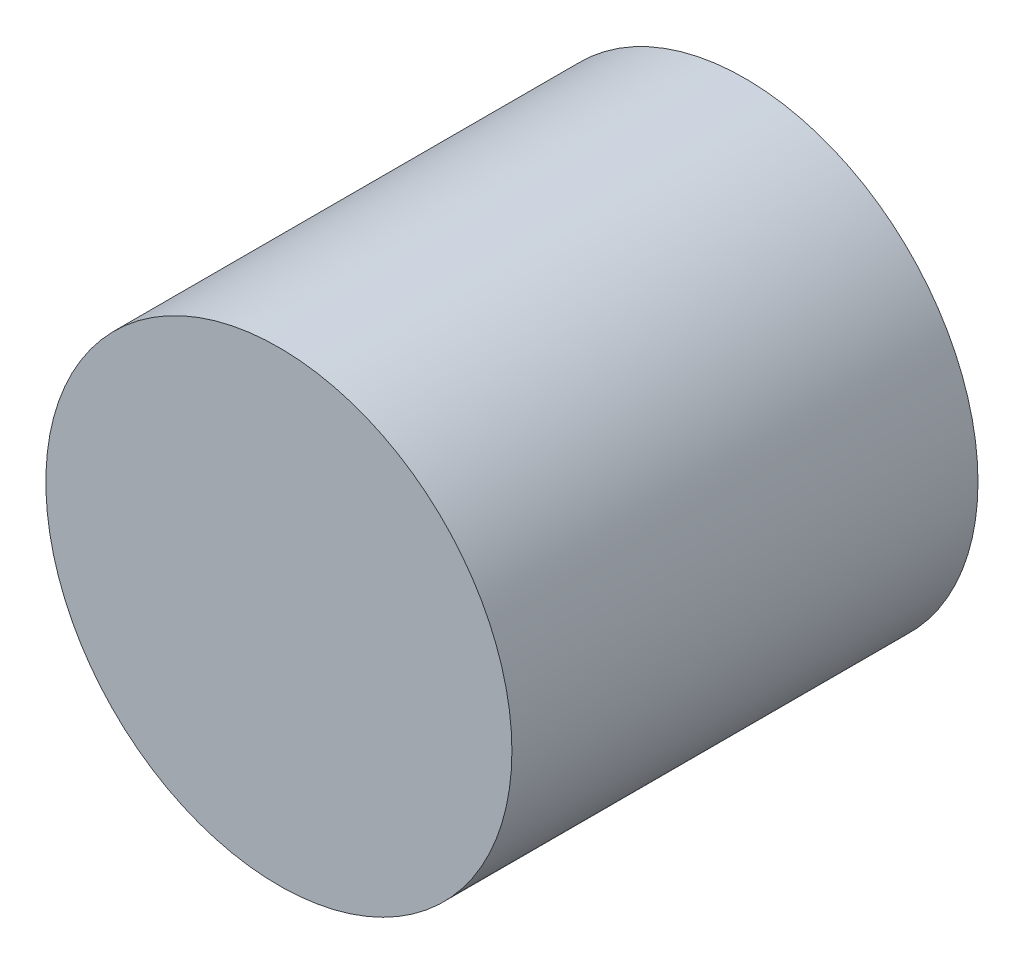
SolidWorks part; units mm, degrees
ref_plane "Front Plane" through (0, 0, 0) normal (0, 0, 1) x (1, 0, 0)
ref_plane "Top Plane" through (0, 0, 0) normal (0, 1, 0) x (1, 0, 0)
ref_plane "Right Plane" through (0, 0, 0) normal (1, 0, 0) x (0, 0, -1)
sketch "Sketch1" plane through (0, 0, 0) normal (0, 0, 1) x (1, 0, 0)
  circle A0 centre (0, 0) radius 3.15
  dimension "D1" = 6.3
extrude "Boss-Extrude1" add sketch "Sketch1" along normal blind 6.3
